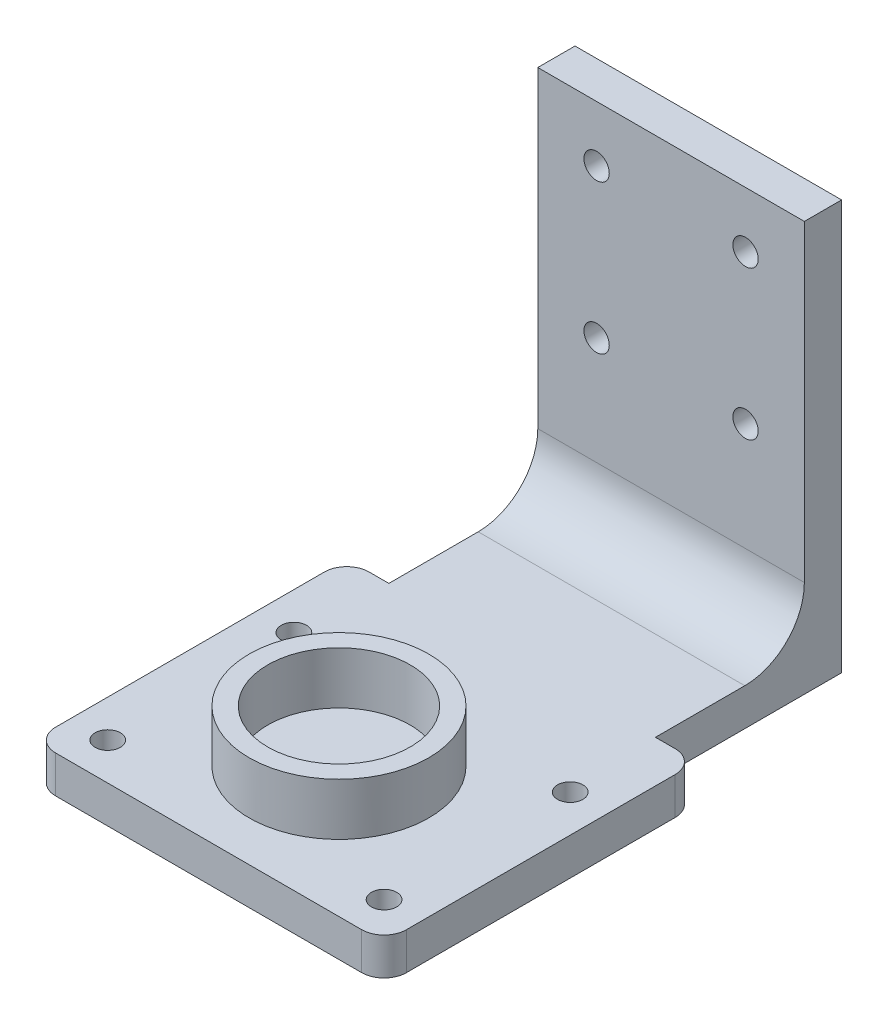
SolidWorks part; units mm, degrees
ref_plane "Front Plane" through (0, 0, 0) normal (0, 0, 1) x (1, 0, 0)
ref_plane "Top Plane" through (0, 0, 0) normal (0, 1, 0) x (1, 0, 0)
ref_plane "Right Plane" through (0, 0, 0) normal (1, 0, 0) x (0, 0, -1)
sketch "Sketch1" plane through (0, 0, 0) normal (0, 1, 0) x (1, 0, 0)
  line L0 (0, 0) -> (0, 44.6) construction
  line L1 (-23.555, 17.5) -> (23.555, 17.5) construction
  line L2 (-23.555, 17.5) -> (-23.555, -17.5)
  line L3 (-23.555, -17.5) -> (23.555, -17.5)
  line L4 (23.555, 17.5) -> (23.555, -17.5)
  line L5 (0, -17.5) -> (0, 17.5) construction
  line L6 (-23.555, 0) -> (23.555, 0) construction
  line L7 (-23.555, 17.5) -> (-23.555, 44.6)
  line L8 (-23.555, 44.6) -> (23.555, 44.6)
  line L9 (23.555, 44.6) -> (23.555, 17.5)
  circle A0 centre (-18.555, -12.5) radius 1.7
  circle A1 centre (-18.555, 12.5) radius 1.7
  circle A2 centre (18.555, -12.5) radius 1.7
  circle A3 centre (18.555, 12.5) radius 1.7
  point P224 (0, 0)
  dimension "D3" = 3.4
  dimension "D1" = 47.11
  dimension "D2" = 35
  dimension "D4" = 5
  dimension "D5" = 5
  dimension "D6" = 44.6
extrude "Boss-Extrude1" add sketch "Sketch1" along normal blind 5
sketch "Sketch2" plane through (0, 5, 0) normal (0, 1, 0) x (1, 0, 0)
  circle A0 centre (0, 0) radius 9.565
  circle A1 centre (0, 0) radius 12.065
  dimension "D1" = 19.13
  dimension "D2" = 2.5
extrude "Boss-Extrude2" add sketch "Sketch2" along normal blind 7
sketch "Sketch3" plane through (0, 0, -44.6) normal (0, 0, -1) x (-1, 0, 0)
  line L0 (-23.555, 0) -> (-23.555, 55)
  line L1 (-23.555, 55) -> (23.555, 55)
  line L2 (23.555, 55) -> (23.555, 0)
  line L3 (23.555, 0) -> (-23.555, 0)
  dimension "D1" = 55
extrude "Boss-Extrude3" add sketch "Sketch3" along normal blind 5
sketch "Sketch4" plane through (0, 0, -49.6) normal (0, 0, -1) x (-1, 0, 0)
  line L1 (-10, 47.5) -> (10, 47.5) construction
  line L2 (-10, 47.5) -> (-10, 27.5) construction
  line L3 (-10, 27.5) -> (10, 27.5) construction
  line L4 (10, 47.5) -> (10, 27.5) construction
  line L5 (0, 27.5) -> (0, 47.5) construction
  line L6 (-10, 37.5) -> (10, 37.5) construction
  line L7 (-23.555, 0) -> (23.555, 0) construction
  circle A0 centre (-10, 47.5) radius 1.7
  circle A1 centre (-10, 27.5) radius 1.7
  circle A2 centre (10, 27.5) radius 1.7
  circle A3 centre (10, 47.5) radius 1.7
  point P172 (0, 37.5)
  dimension "D3" = 3.4
  dimension "D1" = 20
  dimension "D2" = 20
  dimension "D4" = 37.5
extrude "Cut-Extrude1" cut sketch "Sketch4" against normal through all
sketch "Sketch5" plane through (0, 55, 0) normal (0, 1, 0) x (1, 0, 0)
  line L0 (-23.555, 49.6) -> (-23.555, 24.6)
  line L1 (-23.555, 44.6) -> (-23.555, -17.5) construction
  line L2 (-23.555, 24.6) -> (-17.9, 24.6)
  line L3 (-17.9, 24.6) -> (-17.9, 49.6)
  line L4 (-23.555, 49.6) -> (23.555, 49.6) construction
  line L5 (-17.9, 49.6) -> (-23.555, 49.6)
  line L6 (0, 49.6) -> (0, -17.5) construction
  line L7 (-23.555, -17.5) -> (23.555, -17.5) construction
  line L8 (23.555, 49.6) -> (23.555, 24.6)
  line L9 (17.9, 49.6) -> (23.555, 49.6)
  line L10 (17.9, 24.6) -> (17.9, 49.6)
  line L11 (23.555, 24.6) -> (17.9, 24.6)
  dimension "D1" = 25
  dimension "D2" = 35.8
extrude "Cut-Extrude2" cut sketch "Sketch5" against normal through all
fillet "Fillet3" radius 3 4 edges at (23.555, 2.5, -24.6) (23.555, 2.5, 17.5) (-23.555, 2.5, -24.6) (-23.555, 2.5, 17.5)
fillet "Fillet4" radius 8 1 edges at (0, 5, -44.6)
